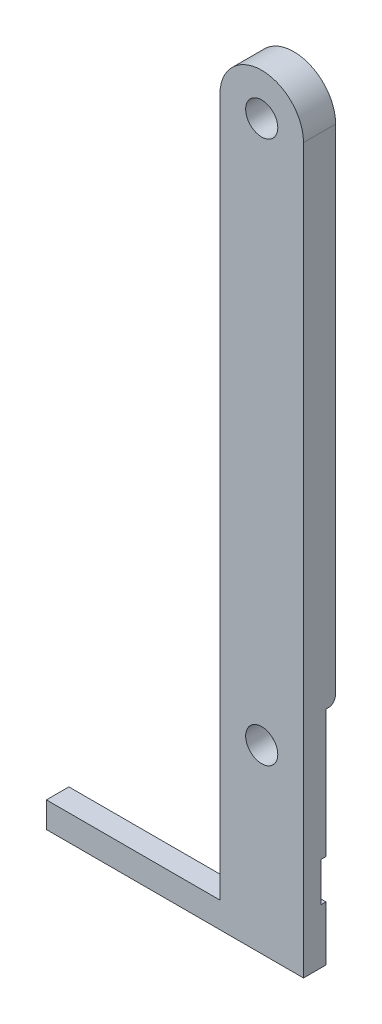
SolidWorks part; units mm, degrees
ref_plane "Front Plane" through (0, 0, 0) normal (0, 0, 1) x (1, 0, 0)
ref_plane "Top Plane" through (0, 0, 0) normal (0, 1, 0) x (1, 0, 0)
ref_plane "Right Plane" through (0, 0, 0) normal (1, 0, 0) x (0, 0, -1)
sketch "Sketch1" plane through (0, 0, 0) normal (0, 0, 1) x (1, 0, 0)
  line L0 (24.475, -28.12) -> (-65.525, -28.12) construction
  line L1 (24.475, -28.12) -> (-65.525, -28.12)
  line L2 (6.5, 84.43) -> (6.5, 0)
  line L3 (6.5, 0) -> (6.5, -28.12)
  line L4 (-6.5, 84.43) -> (-6.5, 0)
  line L5 (-6.5, 0) -> (-6.5, -28.12)
  line L6 (6.5, -24.12) -> (-33.5, -24.12)
  line L7 (-33.5, -24.12) -> (-33.5, -28.12)
  circle A0 centre (0, 84.43) radius 2.5 construction
  circle A1 centre (0, 84.43) radius 2.5
  circle A2 centre (0, 0) radius 2.5 construction
  circle A3 centre (0, 0) radius 2.5
  circle A4 centre (0, 84.43) radius 6.5
  circle A5 centre (0, 0) radius 6.5
  dimension "D3" = 4
  dimension "D4" = 40
  dimension "D1" = 4
  dimension "D2" = 4
extrude "Boss-Extrude1" add sketch "Sketch1" along normal blind 5 contours L6 L7 L1 L5 | L3 L6 L5 L1 | A5 L5 L6 L3 | A5 A3 | A5 L2 A4 L4 | A4 A1
sketch "Sketch2" plane through (0, 0, 0) normal (0, 0, -1) x (-1, 0, 0)
  line L5 (33.5, -24.12) -> (6.5, -24.12)
  line L6 (6.5, -24.12) -> (6.5, 84.43)
  line L7 (-6.5, 84.43) -> (-6.5, -28.12)
  line L8 (-6.5, -28.12) -> (33.5, -28.12)
  line L9 (33.5, -28.12) -> (33.5, -24.12)
  line L10 (33.5, -24.12) -> (6.5, -24.12)
  line L11 (6.5, -24.12) -> (6.5, 84.43)
  line L12 (-6.5, 84.43) -> (-6.5, -28.12)
  line L13 (-6.5, -28.12) -> (33.5, -28.12)
  line L14 (33.5, -28.12) -> (33.5, -24.12)
  arc A0 (7.5998, 5.0052) -> (-9.0301, -1.1258) centre (0, 0) ccw construction
  arc A1 (7.5998, 5.0052) -> (-9.0301, -1.1258) centre (0, 0) ccw
  arc A3 (6.5, 84.43) -> (-6.5, 84.43) centre (0, 84.43) ccw
  arc A4 (6.5, 84.43) -> (-6.5, 84.43) centre (0, 84.43) ccw
  line M7 (33.5, -24.12) -> (6.5, -24.12)
  line M8 (6.5, -24.12) -> (6.5, 84.43)
  line M11 (-6.5, -28.12) -> (33.5, -28.12)
  line M12 (33.5, -28.12) -> (33.5, -24.12)
  circle M13 centre (0, 0) radius 2.5
  dimension "D1" = 0
extrude "Cut-Extrude1" cut sketch "Sketch2" against normal blind 1.5 contours A1 L12 M8 M11 M12 M7 M13
sketch "Sketch3" plane through (0, 0, 1.5) normal (0, 0, -1) x (-1, 0, 0)
  line L0 (-3.475, -13.51) -> (-9.4548, -13.51)
  line L1 (-9.4548, -13.51) -> (-9.4548, -19.61)
  line L2 (-9.4548, -19.61) -> (-3.475, -19.61)
  circle A0 centre (5.525, -18.62) radius 3.05 construction
  circle A1 centre (5.525, -18.62) radius 3.05
  circle A2 centre (-3.475, -16.56) radius 3.05 construction
  circle A3 centre (-3.475, -16.56) radius 3.05
  line M2 (6.5, -24.12) -> (6.5, 6.3687)
  line M4 (-6.5, 6.3687) -> (-6.5, -28.12)
extrude "Cut-Extrude2" cut sketch "Sketch3" against normal blind 0.8 contours A3 M4 | A3 L2 M4 | A3 L0 M4 | A1 M2
fillet "Fillet1" radius 1 1 edges at (0, 9.1, 0)
